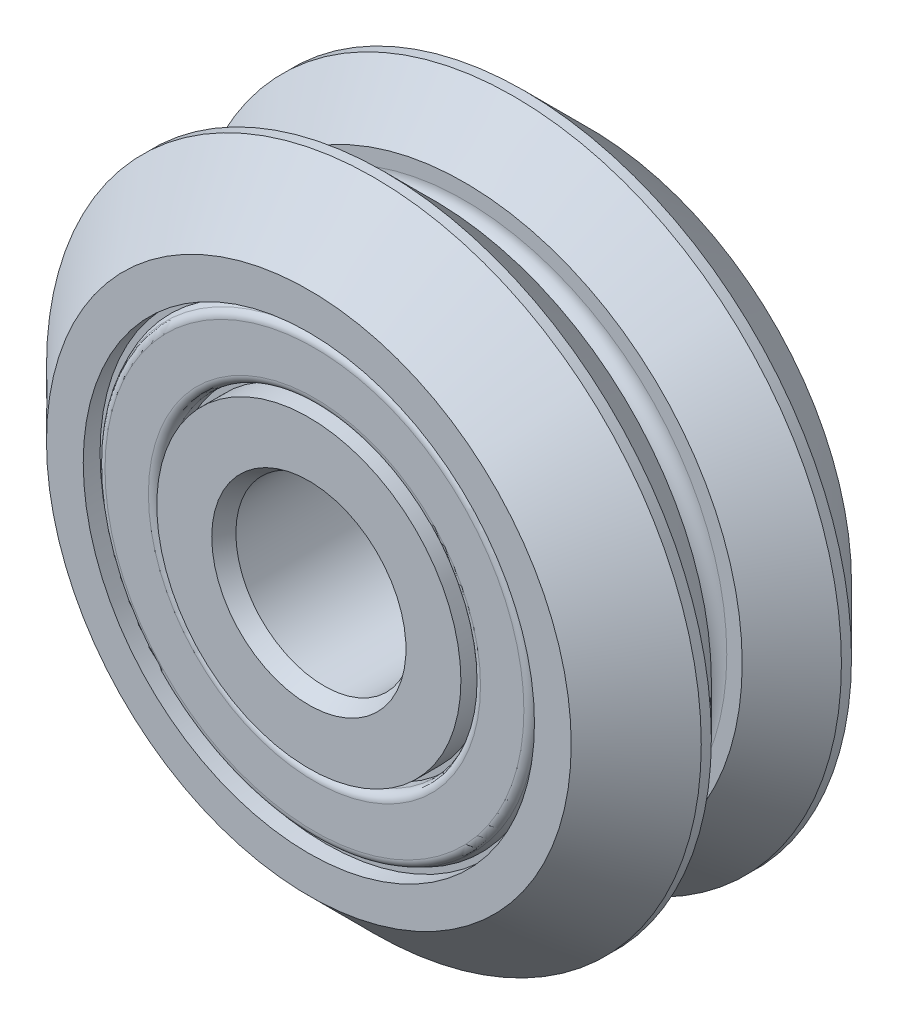
SolidWorks part; units mm, degrees
ref_plane "Front Plane" through (0, 0, 0) normal (0, 0, 1) x (1, 0, 0)
ref_plane "Top Plane" through (0, 0, 0) normal (0, 1, 0) x (1, 0, 0)
ref_plane "Right Plane" through (0, 0, 0) normal (1, 0, 0) x (0, 0, -1)
sketch "Sketch1" plane through (0, 0, 0) normal (1, 0, 0) x (0, 0, -1)
  line L0 (0, 9.1186) -> (0, -9.1186) construction
  line L1 (-3.175, 0) -> (3.175, 0) construction
  line L2 (-3.175, 0) -> (-3.175, 5.9436) construction
  line L3 (-3.175, 5.9436) -> (0, 9.1186) construction
  line L4 (0, 9.1186) -> (3.175, 5.9436) construction
  line L5 (3.175, 5.9436) -> (3.175, 0) construction
  line L6 (-3.175, 5.9436) -> (3.175, 5.9436) construction
  line L7 (0, 5.9436) -> (1.5875, 7.5311) construction
  line L8 (0, 5.9436) -> (-1.5875, 7.5311) construction
  line L9 (-1.7018, 7.4168) -> (1.7018, 7.4168) construction
  line L10 (-3.175, 2) -> (3.175, 2) construction
  line L11 (-3.175, -2) -> (3.175, -2) construction
  line L12 (-1.7018, -7.4168) -> (1.7018, -7.4168) construction
  line L13 (0, -9.1186) -> (-1.5875, -7.5311) construction
  line L14 (0, -9.1186) -> (1.5875, -7.5311) construction
  line L15 (-3.175, -5.9436) -> (3.175, -5.9436) construction
  point P26 (0, -5.9436)
  dimension "Groove Angle" = 90
  dimension "(VRI) Vee Radius Inside" = 5.9436
  dimension "(VRO) Vee Radius Outside" = 9.1186
  dimension "(B) For Shaft Diameter" = 4
  dimension "(D) Roller Diameter" = 14.8336
  dimension "(W) Roller Width" = 6.35
  dimension "Overall Width" = 6.35
  dimension "Groove Depth" = 1.4732
  dimension "Groove Width" = 3.175
sketch "Sketch2" plane through (0, 0, 0) normal (1, 0, 0) x (0, 0, -1)
  line L0 (0, 2) -> (-3.175, 2)
  line L1 (-3.175, 2) -> (3.175, 2) construction
  line L2 (-3.175, 2) -> (-3.175, 5.9436)
  line L3 (-3.175, 0) -> (-3.175, 5.9436) construction
  line L4 (-3.175, 3.4445) -> (0, 3.4445)
  line L5 (0, 9.1186) -> (0, -9.1186) construction
  line L6 (-3.175, 5.9436) -> (-1.7018, 7.4168)
  line L7 (-1.7018, 7.4168) -> (-1.4732, 7.4168)
  line L8 (0, 5.9436) -> (-1.5875, 7.5311) construction
  line L9 (-1.7018, 7.4168) -> (1.7018, 7.4168) construction
  line L10 (-1.4732, 7.4168) -> (-0.3492, 6.2929)
  line L11 (-3.175, 5.1112) -> (-2.6035, 5.1112)
  line L12 (-2.6035, 5.1112) -> (-2.6035, 3.4445)
  line L13 (-0.3492, 5.9436) -> (-0.3492, 6.2929)
  line L14 (0, 9.1186) -> (0, -9.1186) construction
  line L15 (-3.175, 0) -> (3.175, 0) construction
  line L16 (-3.175, 0) -> (3.175, 0) construction
  line L17 (-3.048, 5.1112) -> (-3.175, 5.2382)
  line L18 (-2.794, 5.1112) -> (-2.794, 4.9842)
  line L19 (-2.794, 4.9842) -> (-3.048, 4.8657)
  line L20 (-3.048, 4.8657) -> (-3.048, 3.5715)
  line L21 (-3.048, 3.5715) -> (-2.6035, 3.5715)
  line L22 (-2.794, 3.5715) -> (-2.794, 3.4445) construction
  arc A0 (-0.3492, 5.9436) -> (0, 5.5943) centre (0, 5.9436) ccw
  dimension "D3" = 1.6667
  dimension "D4" = 0.5715
  dimension "D5" = 0.1905
  dimension "D6" = 0.4445
  dimension "D7" = 65
  dimension "D8" = 0.127
  dimension "D2" = 1.4445
  dimension "D1" = 0.6985
  dimension "D9" = 45
sketch "Sketch3" plane through (0, 0, 0) normal (1, 0, 0) x (0, 0, -1)
  line L0 (0, 9.1186) -> (0, -9.1186) construction
  line L1 (0, 2) -> (-3.175, 2) construction
  line L2 (-3.175, 2) -> (-3.175, 5.9436) construction
  line L3 (-3.175, 3.4445) -> (0, 3.4445) construction
  line L4 (0, 3.4445) -> (0, 2)
  line L5 (0, 2) -> (-3.175, 2)
  line L6 (-3.175, 2) -> (-3.175, 3.4445)
  line L7 (-3.175, 3.4445) -> (0, 3.4445)
revolve "Revolve1" add sketch "Sketch3" angle 360 about L16
sketch "Sketch4" plane through (0, 0, 0) normal (1, 0, 0) x (0, 0, -1)
  line L0 (0, 9.1186) -> (0, -9.1186) construction
  line L1 (-0.3492, 5.9436) -> (-0.3492, 6.2929) construction
  line L2 (-1.4732, 7.4168) -> (0, 5.9436) construction
  line L3 (-1.7018, 7.4168) -> (-1.4732, 7.4168) construction
  line L4 (-3.175, 5.9436) -> (-1.7018, 7.4168) construction
  line L5 (-3.175, 2) -> (-3.175, 5.9436) construction
  line L6 (-3.175, 5.1112) -> (-2.6035, 5.1112) construction
  line L7 (-2.6035, 5.1112) -> (-2.6035, 3.4445) construction
  line L8 (-3.175, 3.4445) -> (0, 3.4445) construction
  line L9 (0, 5.5943) -> (0, 3.4445)
  line L10 (-0.3492, 5.9436) -> (-0.3492, 6.2929)
  line L11 (-1.4732, 7.4168) -> (-0.3492, 6.2929)
  line L12 (-1.7018, 7.4168) -> (-1.4732, 7.4168)
  line L13 (-3.175, 5.9436) -> (-1.7018, 7.4168)
  line L14 (-3.175, 5.1112) -> (-3.175, 5.9436)
  line L15 (-3.175, 5.1112) -> (-2.6035, 5.1112)
  line L16 (-2.6035, 5.1112) -> (-2.6035, 3.4445)
  line L17 (-2.6035, 3.4445) -> (0, 3.4445)
  arc A0 (-0.3492, 5.9436) -> (0, 5.5943) centre (0, 5.9436) ccw construction
  arc A1 (-0.3492, 5.9436) -> (0, 5.5943) centre (0, 5.9436) ccw
revolve "Revolve2" add sketch "Sketch4" angle 360 about L16
sketch "Sketch5" plane through (0, 0, 0) normal (1, 0, 0) x (0, 0, -1)
  line L0 (-3.175, 5.1112) -> (-2.6035, 5.1112) construction
  line L1 (-2.6035, 5.1112) -> (-2.6035, 3.4445) construction
  line L2 (-3.048, 3.5715) -> (-2.6035, 3.5715) construction
  line L3 (-3.048, 4.8657) -> (-3.048, 3.5715) construction
  line L4 (-2.794, 4.9842) -> (-3.048, 4.8657) construction
  line L5 (-2.794, 5.1112) -> (-2.794, 4.9842) construction
  line L6 (-2.794, 5.1112) -> (-2.6035, 5.1112)
  line L7 (-2.6035, 5.1112) -> (-2.6035, 3.5715)
  line L8 (-3.048, 3.5715) -> (-2.6035, 3.5715)
  line L9 (-3.048, 4.8657) -> (-3.048, 3.5715)
  line L10 (-2.794, 4.9842) -> (-3.048, 4.8657)
  line L11 (-2.794, 5.1112) -> (-2.794, 4.9842)
revolve "Revolve3" add sketch "Sketch5" angle 360 about L16
chamfer "Chamfer1" distance 0.2 angle 60 1 edges at (2, 0, 3.175)
fillet "Fillet1" radius 0.1905 2 edges at (4.8657, 0, 3.048) (3.5715, 0, 3.048)
mirror "Mirror1" about plane through (0, 0, 0) normal (0, 0, 1) of bodies 104 105
mirror "Mirror2" about plane through (0, 0, 0) normal (0, 0, 1) of bodies 106
equation "\"D3@Sketch2\"=( \"(D) Roller Diameter@Sketch1\" - \"(B) For Shaft Diameter@Sketch1\" )  / 6.5"
equation "\"D2@Sketch2\"=( \"(D) Roller Diameter@Sketch1\" - \"(B) For Shaft Diameter@Sketch1\" )  / 7.5"
equation "\"D1@Sketch2\"=\"(W) Roller Width@Sketch1\"*0.11"
equation "\"D1@Chamfer1\"=\"(B) For Shaft Diameter@Sketch1\"*0.05"
equation "\"D4@Sketch2\"=\"(W) Roller Width@Sketch1\"*0.09"
equation "\"D6@Sketch2\"=\"(W) Roller Width@Sketch1\"*0.07"
equation "\"D5@Sketch2\"=\"(W) Roller Width@Sketch1\"*0.03"
equation "\"D1@Fillet1\"=\"(W) Roller Width@Sketch1\"*0.03"
